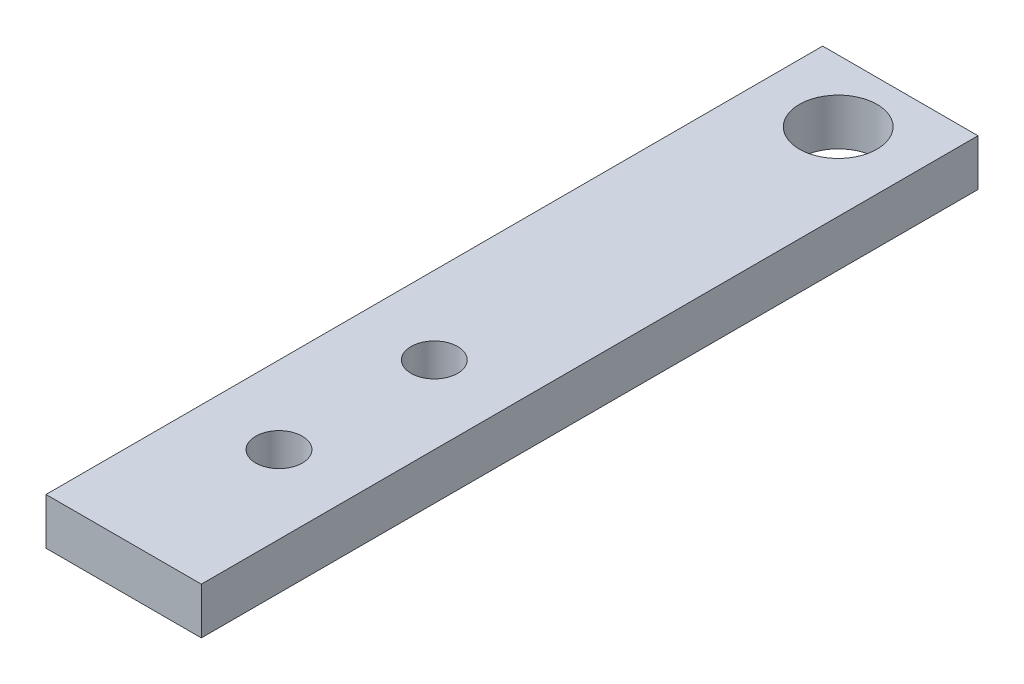
SolidWorks part; units mm, degrees
ref_plane "Front Plane" through (0, 0, 0) normal (0, 0, 1) x (1, 0, 0)
ref_plane "Top Plane" through (0, 0, 0) normal (0, 1, 0) x (1, 0, 0)
ref_plane "Right Plane" through (0, 0, 0) normal (1, 0, 0) x (0, 0, -1)
sketch "Sketch1" plane through (0, 0, 0) normal (0, 1, 0) x (1, 0, 0)
  line L1 (-5, 25) -> (5, 25)
  line L2 (-5, 25) -> (-5, -25)
  line L3 (-5, -25) -> (5, -25)
  line L4 (5, 25) -> (5, -25)
  line L5 (-5, 25) -> (5, -25) construction
  line L6 (-5, -25) -> (5, 25) construction
  circle A0 centre (0, -15) radius 1.5
  circle A1 centre (0, -5) radius 1.5
  circle A2 centre (0, 21) radius 2.5
  point P0 (0, 0)
  dimension "D3" = 3
  dimension "D4" = 10
  dimension "D6" = 5
  dimension "D1" = 50
  dimension "D2" = 10
  dimension "D7" = 4
  dimension "D5" = 2
extrude "Boss-Extrude1" add sketch "Sketch1" along normal blind 3
